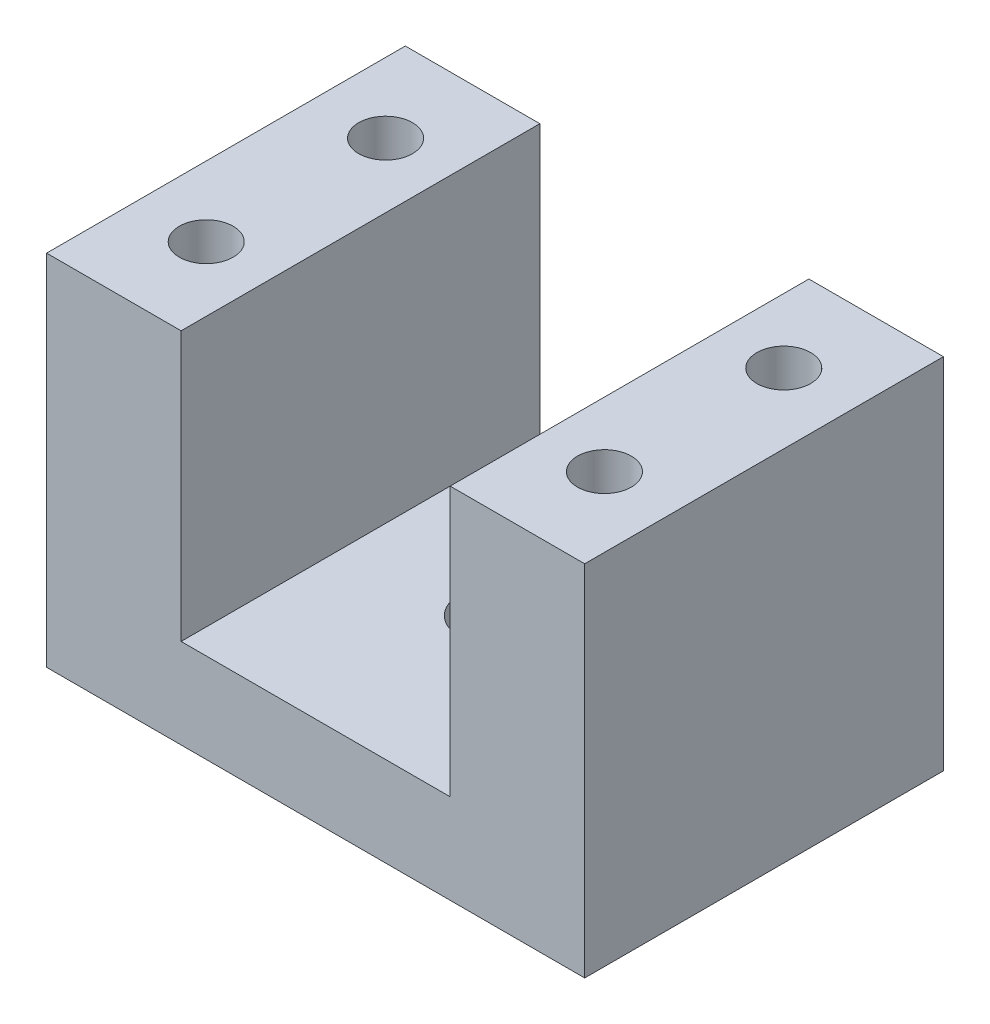
SolidWorks part; units mm, degrees
material "1060 合金"
ref_plane "前视基准面" through (0, 0, 0) normal (0, 0, 1) x (1, 0, 0)
ref_plane "上视基准面" through (0, 0, 0) normal (0, 1, 0) x (1, 0, 0)
ref_plane "右视基准面" through (0, 0, 0) normal (1, 0, 0) x (0, 0, -1)
sketch "草图1" plane through (0, 0, 0) normal (0, 0, 1) x (1, 0, 0)
  line L0 (0, 21.3763) -> (0, -7.9965) construction
  line L1 (7.5, 0) -> (-7.5, 0)
  line L2 (-7.5, 0) -> (-7.5, 15)
  line L3 (-7.5, 15) -> (-15, 15)
  line L4 (-15, 15) -> (-15, -5)
  line L5 (-15, -5) -> (15, -5)
  line L6 (15, 15) -> (15, -5)
  line L7 (7.5, 15) -> (15, 15)
  line L8 (7.5, 0) -> (7.5, 15)
  point P10 (0, -5)
  point P13 (0, 0)
  dimension "D1" = 30
  dimension "D2" = 15
  dimension "D3" = 5
  dimension "D4" = 15
extrude "凸台-拉伸1" add sketch "草图1" along normal mid plane 20
sketch "草图2" plane through (0, 15, 0) normal (0, 1, 0) x (1, 0, 0)
  line L0 (-15, 0) -> (15, 0) construction
  line L1 (-15, -10) -> (-15, 10) construction
  line L2 (15, -10) -> (15, 10) construction
  circle A0 centre (-11.1, 5) radius 1.5
  circle A1 centre (11.1, -5) radius 1.5
  circle A2 centre (11.1, 5) radius 1.5
  circle A3 centre (-11.1, -5) radius 1.5
  dimension "D1" = 3
  dimension "D2" = 10
  dimension "D3" = 22.2
  dimension "D4" = 5
  dimension "D5" = 11.1
extrude "切除-拉伸1" cut sketch "草图2" against normal blind 10
sketch "草图3" plane through (0, 0, 0) normal (0, 1, 0) x (1, 0, 0)
  circle A0 centre (0, 0) radius 2
  dimension "D1" = 4
extrude "切除-拉伸2" cut sketch "草图3" against normal up to next
